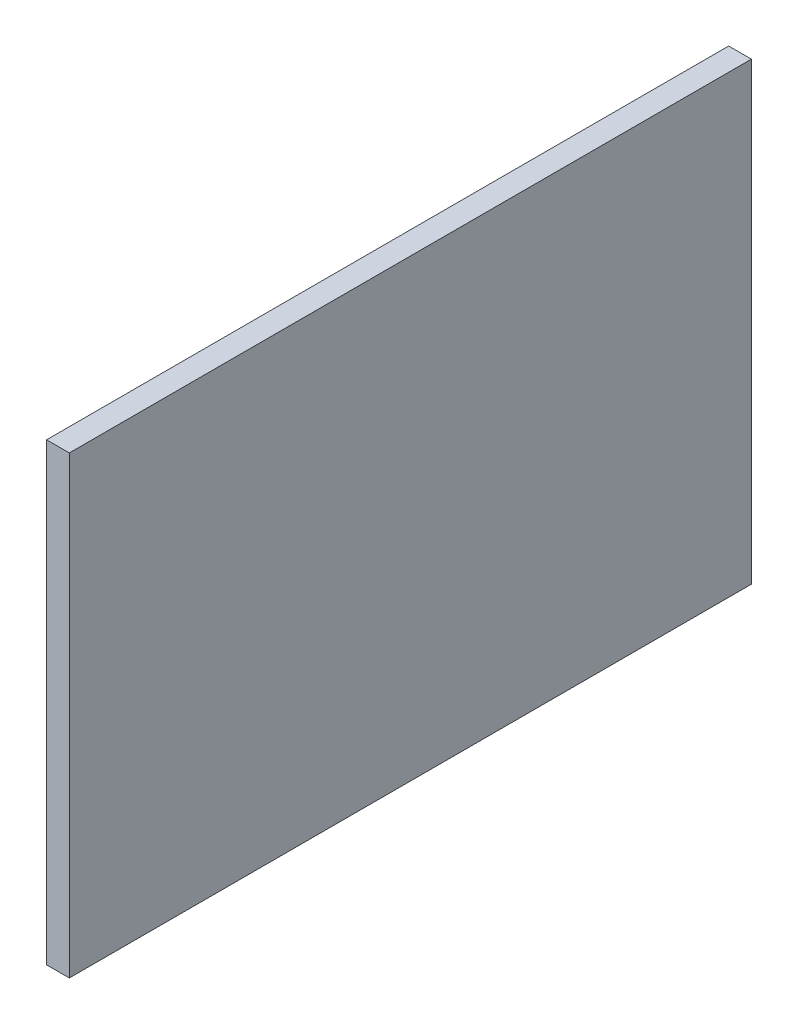
SolidWorks part; units mm, degrees
ref_plane "Alzado" through (0, 0, 0) normal (0, 0, 1) x (1, 0, 0)
ref_plane "Planta" through (0, 0, 0) normal (0, 1, 0) x (1, 0, 0)
ref_plane "Vista lateral" through (0, 0, 0) normal (1, 0, 0) x (0, 0, -1)
sketch "Croquis2" plane through (0, 0, 0) normal (0, 0, 1) x (1, 0, 0)
  line L1 (0, 0) -> (10, 0)
  line L2 (0, 0) -> (0, 200)
  line L3 (0, 200) -> (10, 200)
  line L4 (10, 0) -> (10, 200)
extrude "Saliente-Extruir1" add sketch "Croquis2" along normal blind 300
